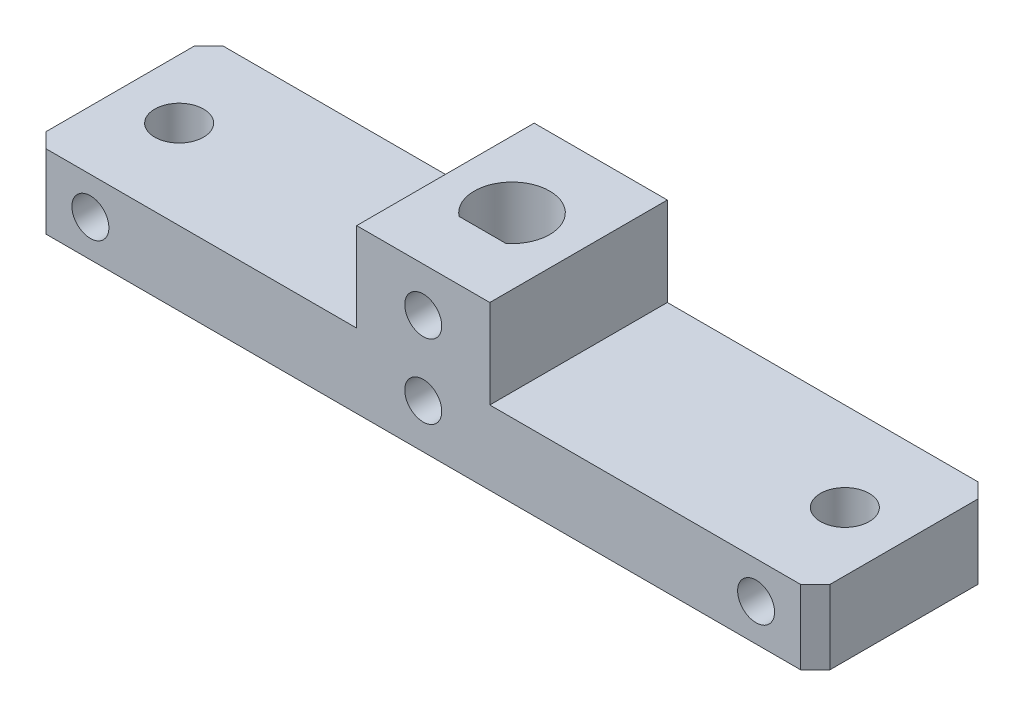
SolidWorks part; units mm, degrees
ref_plane "Top" through (0, 0, 0) normal (0, 0, 1) x (1, 0, 0)
ref_plane "Front" through (0, 0, 0) normal (0, 1, 0) x (1, 0, 0)
ref_plane "Right" through (0, 0, 0) normal (1, 0, 0) x (0, 0, -1)
sketch "Body Sketch" plane through (0, 0, 0) normal (0, 0, 1) x (1, 0, 0)
  line L0 (-26.5, 0) -> (26.5, 0)
  line L1 (26.5, 0) -> (26.5, 5)
  line L2 (26.5, 5) -> (4.5, 5)
  line L3 (4.5, 5) -> (4.5, 11)
  line L4 (4.5, 11) -> (-4.5, 11)
  line L5 (-4.5, 11) -> (-4.5, 5)
  line L6 (-4.5, 5) -> (-26.5, 5)
  line L7 (-26.5, 5) -> (-26.5, 0)
  point P8 (0, 0)
  dimension "D1" = 53
  dimension "D2" = 9
  dimension "D3" = 5
  dimension "D4" = 6
extrude "Body Extrude" add sketch "Body Sketch" against normal blind 12
sketch "Sketch2" plane through (0, 0, 0) normal (0, 1, 0) x (1, 0, 0)
  line L0 (-22.5, 6) -> (22.5, 6) construction
  line L1 (-1.5819, 4) -> (1.5819, 4)
  line L2 (0, 4) -> (0, 8.55) construction
  arc A2 (1.5819, 4) -> (-1.5819, 4) centre (0, 6) ccw
  point P8 (0, 6)
  dimension "D3" = 5.1
  dimension "D1" = 6
  dimension "D2" = 45
  dimension "D4" = 4.55
hole_wizard "M4x0.7 Tapped Hole6" positions "Sketch5" profile "Sketch6" tap size "M4x0.7" standard "ANSI Metric" end condition up to next
sketch "Sketch5" plane through (0, 0, 0) normal (0, 1, 0) x (1, 0, 0)
  line L0 (-22.5, 6) -> (22.5, 6) construction
  line L2 (0, 0) -> (0, 6) construction
  point P0 (-22.5, 6)
  point P2 (22.5, 6)
  dimension "D1" = 45
  dimension "D2" = 6
cosmetic thread "Hole Thread1"
cosmetic thread "Hole Thread2"
sketch "Sketch6" plane through (-22.5, 0, -6) normal (1, 0, 0) x (0, 0, -1)
  line L0 (0, 0) -> (0, 5)
  line L1 (0, 5) -> (1.65, 5)
  line L2 (1.65, 5) -> (1.65, 0)
  line L5 (1.65, 0) -> (0, 0)
  line L11 (0, -6.35) -> (0, 107.95) construction
  dimension "Thru Tap Drill Dia." = 3.3
  dimension "Thru Tap Drill Depth" = 5
extrude "Cut-Extrude1" cut sketch "Sketch2" along normal through all
hole_wizard "M3x0.5 Tapped Hole1" positions "Sketch7" profile "Sketch8" tap size "M3x0.5" standard "ANSI Metric"
sketch "Sketch7" plane through (0, 0, 0) normal (0, 0, 1) x (1, 0, 0)
  line L0 (-26.5, 5) -> (-26.5, 0) construction
  line L1 (-26.5, 2.5) -> (26.5, 2.5) construction
  line L2 (26.5, 0) -> (26.5, 5) construction
  line L4 (0, 0) -> (0, 11) construction
  line L5 (4.5, 11) -> (-4.5, 11) construction
  point P0 (-22.5, 2.5)
  point P2 (22.5, 2.5)
  point P4 (0, 8)
  point P6 (0, 3)
  dimension "D1" = 3
  dimension "D2" = 3
  dimension "D3" = 45
sketch "Sketch8" plane through (-22.5, 2.5, 0) normal (1, 0, 0) x (0, -1, 0)
  line L0 (0, 0) -> (0, 4.35)
  line L1 (0, 4.35) -> (1.25, 4.35)
  line L2 (1.25, 4.35) -> (1.25, 0)
  line L5 (1.25, 0) -> (0, 0)
  line L11 (0, -6.35) -> (0, 107.95) construction
  dimension "Thru Tap Drill Dia." = 2.5
  dimension "Thru Tap Drill Depth" = 4.35
cosmetic thread "Hole Thread3"
cosmetic thread "Hole Thread4"
cosmetic thread "Hole Thread5"
cosmetic thread "Hole Thread6"
chamfer "Chamfer1" distance 1 angle 45 4 edges at (-26.5, 2.5, -12) (-26.5, 2.5, 0) (26.5, 2.5, -12) (26.5, 2.5, 0)
equation "\"Height\"= 12mm"
equation "\"D1@Body Extrude\"=\"Height\""
equation "\"D1@Sketch2\"=0.5*\"Height\""
equation "\"D2@Sketch5\"=0.5*\"Height\""
